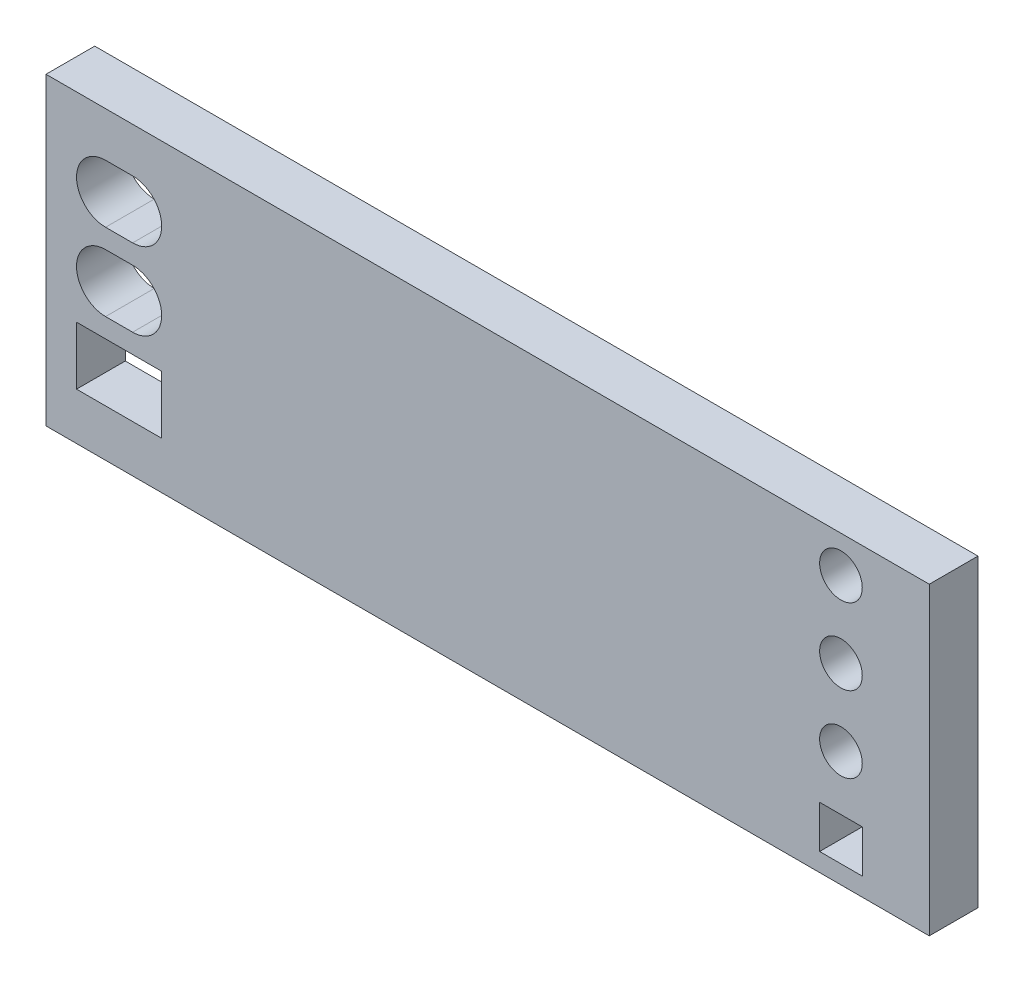
SolidWorks part; units mm, degrees
ref_plane "Plan de face" through (0, 0, 0) normal (0, 0, 1) x (1, 0, 0)
ref_plane "Plan de dessus" through (0, 0, 0) normal (0, 1, 0) x (1, 0, 0)
ref_plane "Plan de droite" through (0, 0, 0) normal (1, 0, 0) x (0, 0, -1)
sketch "Model" plane through (0, 0, 0) normal (0, 0, 1) x (1, 0, 0)
  line L0 (9.325, 6.625) -> (8.275, 6.625) construction
  line L1 (8.275, 7.075) -> (9.325, 7.075) construction
  line L2 (9.325, 5.975) -> (8.275, 5.975) construction
  line L3 (8.275, 6.425) -> (9.325, 6.425) construction
  line L4 (9.325, 5.325) -> (8.275, 5.325) construction
  line L5 (8.275, 5.775) -> (9.325, 5.775) construction
  line L6 (9.325, 4.675) -> (8.275, 4.675) construction
  line L7 (8.275, 5.125) -> (9.325, 5.125) construction
  line L8 (9.325, 4.025) -> (8.275, 4.025) construction
  line L9 (8.275, 4.475) -> (9.325, 4.475) construction
  line L10 (9.325, 3.375) -> (8.275, 3.375) construction
  line L11 (8.275, 3.825) -> (9.325, 3.825) construction
  line L12 (9.325, 2.725) -> (8.275, 2.725) construction
  line L13 (8.275, 3.175) -> (9.325, 3.175) construction
  line L14 (15.125, 2.725) -> (14.075, 2.725) construction
  line L15 (14.075, 3.175) -> (15.125, 3.175) construction
  line L16 (15.125, 3.375) -> (14.075, 3.375) construction
  line L17 (14.075, 3.825) -> (15.125, 3.825) construction
  line L18 (15.125, 4.025) -> (14.075, 4.025) construction
  line L19 (14.075, 4.475) -> (15.125, 4.475) construction
  line L20 (15.125, 4.675) -> (14.075, 4.675) construction
  line L21 (14.075, 5.125) -> (15.125, 5.125) construction
  line L22 (15.125, 5.325) -> (14.075, 5.325) construction
  line L23 (14.075, 5.775) -> (15.125, 5.775) construction
  line L24 (15.125, 5.975) -> (14.075, 5.975) construction
  line L25 (14.075, 6.425) -> (15.125, 6.425) construction
  line L26 (15.125, 6.625) -> (14.075, 6.625) construction
  line L27 (14.075, 7.075) -> (15.125, 7.075) construction
  line L28 (17.725, 9.3) -> (18.675, 9.3) construction
  line L29 (18.675, 9.3) -> (18.675, 8.3) construction
  line L30 (18.675, 8.3) -> (17.725, 8.3) construction
  line L31 (17.725, 8.3) -> (17.725, 9.3) construction
  line L32 (16.125, 9.3) -> (17.075, 9.3) construction
  line L33 (17.075, 9.3) -> (17.075, 8.3) construction
  line L34 (17.075, 8.3) -> (16.125, 8.3) construction
  line L35 (16.125, 8.3) -> (16.125, 9.3) construction
  line L36 (18.525, 2) -> (19.475, 2) construction
  line L37 (19.475, 2) -> (19.475, 1) construction
  line L38 (19.475, 1) -> (18.525, 1) construction
  line L39 (18.525, 1) -> (18.525, 2) construction
  line L40 (16.925, 2) -> (17.875, 2) construction
  line L41 (17.875, 2) -> (17.875, 1) construction
  line L42 (17.875, 1) -> (16.925, 1) construction
  line L43 (16.925, 1) -> (16.925, 2) construction
  line L44 (17.875, 6.5) -> (16.925, 6.5) construction
  line L45 (16.925, 6.5) -> (16.925, 7.5) construction
  line L46 (16.925, 7.5) -> (17.875, 7.5) construction
  line L47 (17.875, 7.5) -> (17.875, 6.5) construction
  line L48 (19.475, 6.5) -> (18.525, 6.5) construction
  line L49 (18.525, 6.5) -> (18.525, 7.5) construction
  line L50 (18.525, 7.5) -> (19.475, 7.5) construction
  line L51 (19.475, 7.5) -> (19.475, 6.5) construction
  line L52 (7.3, 7.675) -> (7.3, 6.725) construction
  line L53 (7.3, 6.725) -> (6.3, 6.725) construction
  line L54 (6.3, 6.725) -> (6.3, 7.675) construction
  line L55 (6.3, 7.675) -> (7.3, 7.675) construction
  line L56 (7.3, 9.275) -> (7.3, 8.325) construction
  line L57 (7.3, 8.325) -> (6.3, 8.325) construction
  line L58 (6.3, 8.325) -> (6.3, 9.275) construction
  line L59 (6.3, 9.275) -> (7.3, 9.275) construction
  line L60 (16.9, 4.725) -> (16.9, 5.675) construction
  line L61 (16.9, 5.675) -> (17.9, 5.675) construction
  line L62 (17.9, 5.675) -> (17.9, 4.725) construction
  line L63 (17.9, 4.725) -> (16.9, 4.725) construction
  line L64 (16.9, 3.125) -> (16.9, 4.075) construction
  line L65 (16.9, 4.075) -> (17.9, 4.075) construction
  line L66 (17.9, 4.075) -> (17.9, 3.125) construction
  line L67 (17.9, 3.125) -> (16.9, 3.125) construction
  line L68 (19.5, 4.075) -> (19.5, 3.125) construction
  line L69 (19.5, 3.125) -> (18.5, 3.125) construction
  line L70 (18.5, 3.125) -> (18.5, 4.075) construction
  line L71 (18.5, 4.075) -> (19.5, 4.075) construction
  line L72 (19.5, 5.675) -> (19.5, 4.725) construction
  line L73 (19.5, 4.725) -> (18.5, 4.725) construction
  line L74 (18.5, 4.725) -> (18.5, 5.675) construction
  line L75 (18.5, 5.675) -> (19.5, 5.675) construction
  line L76 (7.475, 0.8) -> (6.525, 0.8) construction
  line L77 (6.525, 0.8) -> (6.525, 1.8) construction
  line L78 (6.525, 1.8) -> (7.475, 1.8) construction
  line L79 (7.475, 1.8) -> (7.475, 0.8) construction
  line L80 (9.075, 0.8) -> (8.125, 0.8) construction
  line L81 (8.125, 0.8) -> (8.125, 1.8) construction
  line L82 (8.125, 1.8) -> (9.075, 1.8) construction
  line L83 (9.075, 1.8) -> (9.075, 0.8) construction
  line L84 (13.775, 0.8) -> (12.825, 0.8) construction
  line L85 (12.825, 0.8) -> (12.825, 1.8) construction
  line L86 (12.825, 1.8) -> (13.775, 1.8) construction
  line L87 (13.775, 1.8) -> (13.775, 0.8) construction
  line L88 (15.375, 0.8) -> (14.425, 0.8) construction
  line L89 (14.425, 0.8) -> (14.425, 1.8) construction
  line L90 (14.425, 1.8) -> (15.375, 1.8) construction
  line L91 (15.375, 1.8) -> (15.375, 0.8) construction
  line L92 (9.725, 9.3) -> (10.675, 9.3) construction
  line L93 (10.675, 9.3) -> (10.675, 8.3) construction
  line L94 (10.675, 8.3) -> (9.725, 8.3) construction
  line L95 (9.725, 8.3) -> (9.725, 9.3) construction
  line L96 (8.125, 9.3) -> (9.075, 9.3) construction
  line L97 (9.075, 9.3) -> (9.075, 8.3) construction
  line L98 (9.075, 8.3) -> (8.125, 8.3) construction
  line L99 (8.125, 8.3) -> (8.125, 9.3) construction
  line L100 (13.275, 8.3) -> (12.325, 8.3) construction
  line L101 (12.325, 8.3) -> (12.325, 9.3) construction
  line L102 (12.325, 9.3) -> (13.275, 9.3) construction
  line L103 (13.275, 9.3) -> (13.275, 8.3) construction
  line L104 (14.875, 8.3) -> (13.925, 8.3) construction
  line L105 (13.925, 8.3) -> (13.925, 9.3) construction
  line L106 (13.925, 9.3) -> (14.875, 9.3) construction
  line L107 (14.875, 9.3) -> (14.875, 8.3) construction
  line L108 (7.3, 4.575) -> (7.3, 3.625) construction
  line L109 (7.3, 3.625) -> (6.3, 3.625) construction
  line L110 (6.3, 3.625) -> (6.3, 4.575) construction
  line L111 (6.3, 4.575) -> (7.3, 4.575) construction
  line L112 (7.3, 6.175) -> (7.3, 5.225) construction
  line L113 (7.3, 5.225) -> (6.3, 5.225) construction
  line L114 (6.3, 5.225) -> (6.3, 6.175) construction
  line L115 (6.3, 6.175) -> (7.3, 6.175) construction
  line L116 (23.3, 8.225) -> (23.3, 9.175) construction
  line L117 (23.3, 9.175) -> (24.3, 9.175) construction
  line L118 (24.3, 9.175) -> (24.3, 8.225) construction
  line L119 (24.3, 8.225) -> (23.3, 8.225) construction
  line L120 (23.3, 6.625) -> (23.3, 7.575) construction
  line L121 (23.3, 7.575) -> (24.3, 7.575) construction
  line L122 (24.3, 7.575) -> (24.3, 6.625) construction
  line L123 (24.3, 6.625) -> (23.3, 6.625) construction
  line L124 (21.7, 8.225) -> (21.7, 9.175) construction
  line L125 (21.7, 9.175) -> (22.7, 9.175) construction
  line L126 (22.7, 9.175) -> (22.7, 8.225) construction
  line L127 (22.7, 8.225) -> (21.7, 8.225) construction
  line L128 (21.7, 6.625) -> (21.7, 7.575) construction
  line L129 (21.7, 7.575) -> (22.7, 7.575) construction
  line L130 (22.7, 7.575) -> (22.7, 6.625) construction
  line L131 (22.7, 6.625) -> (21.7, 6.625) construction
  line L132 (22.675, 0.7) -> (21.725, 0.7) construction
  line L133 (21.725, 0.7) -> (21.725, 1.7) construction
  line L134 (21.725, 1.7) -> (22.675, 1.7) construction
  line L135 (22.675, 1.7) -> (22.675, 0.7) construction
  line L136 (24.275, 0.7) -> (23.325, 0.7) construction
  line L137 (23.325, 0.7) -> (23.325, 1.7) construction
  line L138 (23.325, 1.7) -> (24.275, 1.7) construction
  line L139 (24.275, 1.7) -> (24.275, 0.7) construction
  line L140 (22.05, 2.35) -> (21.45, 2.35) construction
  line L141 (21.45, 2.35) -> (21.45, 3.45) construction
  line L142 (21.45, 3.45) -> (22.05, 3.45) construction
  line L143 (22.05, 3.45) -> (22.05, 2.35) construction
  line L144 (23, 2.35) -> (22.4, 2.35) construction
  line L145 (22.4, 2.35) -> (22.4, 3.45) construction
  line L146 (22.4, 3.45) -> (23, 3.45) construction
  line L147 (23, 3.45) -> (23, 2.35) construction
  line L148 (23.95, 2.35) -> (23.35, 2.35) construction
  line L149 (23.35, 2.35) -> (23.35, 3.45) construction
  line L150 (23.35, 3.45) -> (23.95, 3.45) construction
  line L151 (23.95, 3.45) -> (23.95, 2.35) construction
  line L152 (23.95, 4.95) -> (23.35, 4.95) construction
  line L153 (23.35, 4.95) -> (23.35, 6.05) construction
  line L154 (23.35, 6.05) -> (23.95, 6.05) construction
  line L155 (23.95, 6.05) -> (23.95, 4.95) construction
  line L156 (22.05, 4.95) -> (21.45, 4.95) construction
  line L157 (21.45, 4.95) -> (21.45, 6.05) construction
  line L158 (21.45, 6.05) -> (22.05, 6.05) construction
  line L159 (22.05, 6.05) -> (22.05, 4.95) construction
  line L160 (3.797, 1.5475) -> (1.003, 1.5475)
  line L161 (1.003, 1.5475) -> (1.003, 3.4525)
  line L162 (1.003, 3.4525) -> (3.797, 3.4525)
  line L163 (3.797, 3.4525) -> (3.797, 1.5475)
  line L164 (1.9555, 5.9925) -> (2.8445, 5.9925)
  line L165 (2.8445, 4.0875) -> (1.9555, 4.0875)
  line L166 (1.9555, 8.5325) -> (2.8445, 8.5325)
  line L167 (2.8445, 6.6275) -> (1.9555, 6.6275)
  line L168 (26.8, 0.6) -> (25.4, 0.6)
  line L169 (25.4, 0.6) -> (25.4, 2)
  line L170 (25.4, 2) -> (26.8, 2)
  line L171 (26.8, 2) -> (26.8, 0.6)
  line L172 (0, 0) -> (0, 10)
  line L173 (0, 10) -> (29, 10)
  line L174 (29, 10) -> (29, 0)
  line L175 (29, 0) -> (0, 0)
  circle A0 centre (26.1, 3.8) radius 0.7
  circle A1 centre (26.1, 6.3) radius 0.7
  circle A2 centre (26.1, 8.8) radius 0.7
  arc A3 (8.275, 7.075) -> (8.275, 6.625) centre (8.275, 6.85) ccw construction
  arc A4 (9.325, 6.625) -> (9.325, 7.075) centre (9.325, 6.85) ccw construction
  arc A5 (8.275, 6.425) -> (8.275, 5.975) centre (8.275, 6.2) ccw construction
  arc A6 (9.325, 5.975) -> (9.325, 6.425) centre (9.325, 6.2) ccw construction
  arc A7 (8.275, 5.775) -> (8.275, 5.325) centre (8.275, 5.55) ccw construction
  arc A8 (9.325, 5.325) -> (9.325, 5.775) centre (9.325, 5.55) ccw construction
  arc A9 (8.275, 5.125) -> (8.275, 4.675) centre (8.275, 4.9) ccw construction
  arc A10 (9.325, 4.675) -> (9.325, 5.125) centre (9.325, 4.9) ccw construction
  arc A11 (8.275, 4.475) -> (8.275, 4.025) centre (8.275, 4.25) ccw construction
  arc A12 (9.325, 4.025) -> (9.325, 4.475) centre (9.325, 4.25) ccw construction
  arc A13 (8.275, 3.825) -> (8.275, 3.375) centre (8.275, 3.6) ccw construction
  arc A14 (9.325, 3.375) -> (9.325, 3.825) centre (9.325, 3.6) ccw construction
  arc A15 (8.275, 3.175) -> (8.275, 2.725) centre (8.275, 2.95) ccw construction
  arc A16 (9.325, 2.725) -> (9.325, 3.175) centre (9.325, 2.95) ccw construction
  arc A17 (14.075, 3.175) -> (14.075, 2.725) centre (14.075, 2.95) ccw construction
  arc A18 (15.125, 2.725) -> (15.125, 3.175) centre (15.125, 2.95) ccw construction
  arc A19 (14.075, 3.825) -> (14.075, 3.375) centre (14.075, 3.6) ccw construction
  arc A20 (15.125, 3.375) -> (15.125, 3.825) centre (15.125, 3.6) ccw construction
  arc A21 (14.075, 4.475) -> (14.075, 4.025) centre (14.075, 4.25) ccw construction
  arc A22 (15.125, 4.025) -> (15.125, 4.475) centre (15.125, 4.25) ccw construction
  arc A23 (14.075, 5.125) -> (14.075, 4.675) centre (14.075, 4.9) ccw construction
  arc A24 (15.125, 4.675) -> (15.125, 5.125) centre (15.125, 4.9) ccw construction
  arc A25 (14.075, 5.775) -> (14.075, 5.325) centre (14.075, 5.55) ccw construction
  arc A26 (15.125, 5.325) -> (15.125, 5.775) centre (15.125, 5.55) ccw construction
  arc A27 (14.075, 6.425) -> (14.075, 5.975) centre (14.075, 6.2) ccw construction
  arc A28 (15.125, 5.975) -> (15.125, 6.425) centre (15.125, 6.2) ccw construction
  arc A29 (14.075, 7.075) -> (14.075, 6.625) centre (14.075, 6.85) ccw construction
  arc A30 (15.125, 6.625) -> (15.125, 7.075) centre (15.125, 6.85) ccw construction
  arc A31 (2.8445, 4.0875) -> (2.8445, 5.9925) centre (2.8445, 5.04) ccw
  arc A32 (1.9555, 5.9925) -> (1.9555, 4.0875) centre (1.9555, 5.04) ccw
  arc A33 (2.8445, 6.6275) -> (2.8445, 8.5325) centre (2.8445, 7.58) ccw
  arc A34 (1.9555, 8.5325) -> (1.9555, 6.6275) centre (1.9555, 7.58) ccw
extrude "Boss.-Extru.1" add sketch "Model" along normal blind 1.6
